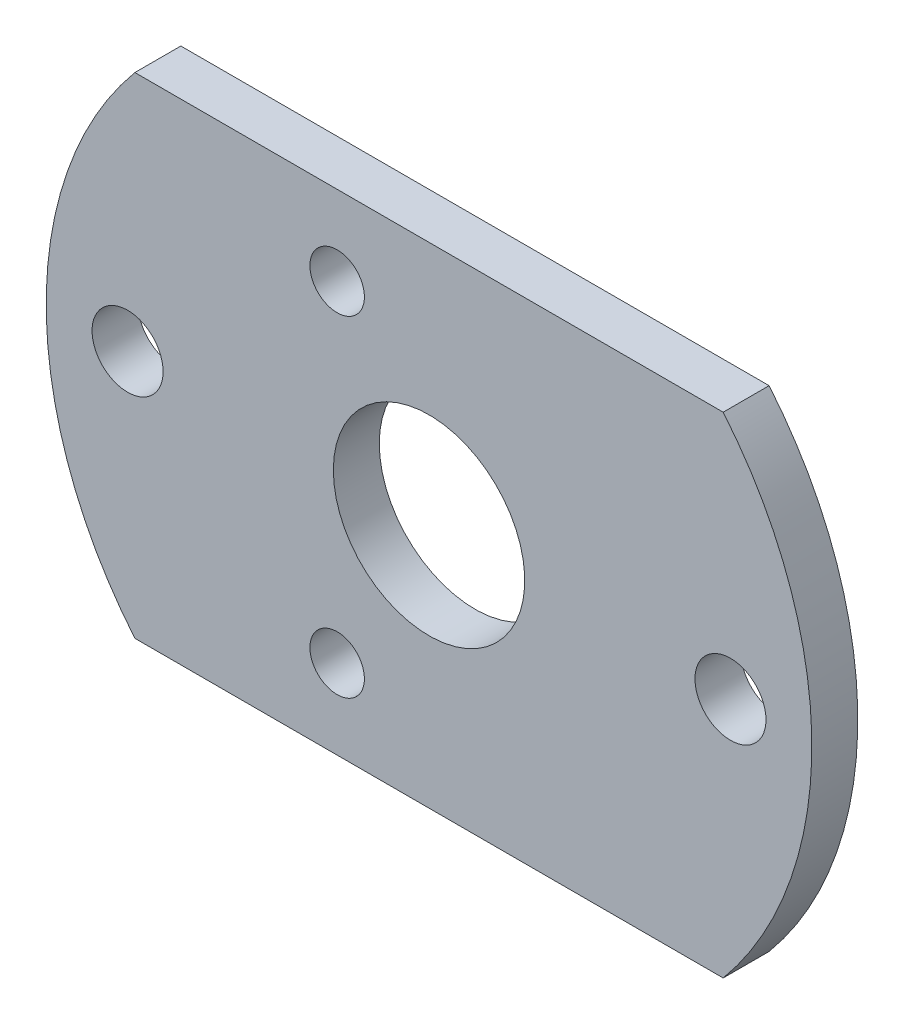
SolidWorks part; units mm, degrees
material "Cast Alloy Steel"
ref_plane "Front Plane" through (0, 0, 0) normal (0, 0, 1) x (1, 0, 0)
ref_plane "Top Plane" through (0, 0, 0) normal (0, 1, 0) x (1, 0, 0)
ref_plane "Right Plane" through (0, 0, 0) normal (1, 0, 0) x (0, 0, -1)
sketch "Sketch1" plane through (0, 0, 0) normal (0, 0, 1) x (1, 0, 0)
  circle A0 centre (0, 0) radius 15.875
  circle A1 centre (0, 0) radius 3.9688
  dimension "D1" = 7.9375
  dimension "D2" = 31.75
extrude "Boss-Extrude1" add sketch "Sketch1" along normal blind 1.905
hole_wizard "MotorClearanceHoles" positions "Sketch5" profile "Sketch4" hole size "#4" standard "ANSI Inch" end condition through all
sketch "Sketch5" plane through (0, 0, 1.905) normal (0, 0, 1) x (1, 0, 0)
  line L0 (0, 0) -> (0, 12.3097) construction
  point P0 (-12.5, 0)
  point P2 (12.5, 0)
  dimension "D1" = 25
sketch "Sketch4" plane through (-12.5, 0, 1.905) normal (1, 0, 0) x (0, -1, 0)
  line L0 (0, 0) -> (0, 1.905)
  line L1 (0, 1.905) -> (1.4732, 1.905)
  line L2 (1.4732, 1.905) -> (1.4732, 0)
  line L5 (1.4732, 0) -> (0, 0)
  line L11 (0, -6.35) -> (0, 107.95) construction
  dimension "Thru Hole Dia." = 2.9464
  dimension "Thru Hole Depth" = 1.905
hole_wizard "EncoderSetScrews" positions "Sketch7" profile "Sketch6" tap size "#4-40" standard "ANSI Inch" end condition through all
sketch "Sketch7" plane through (0, 0, 1.905) normal (0, 0, 1) x (1, 0, 0)
  line L0 (-21.019, 0) -> (-19.6675, 0) construction
  point P0 (-3.81, 6.858)
  point P2 (-3.81, -6.858)
  dimension "D1" = 13.716
  dimension "D2" = 3.81
sketch "Sketch6" plane through (-3.81, 6.858, 1.905) normal (1, 0, 0) x (0, -1, 0)
  line L0 (0, 0) -> (0, 1.905)
  line L1 (0, 1.905) -> (1.1303, 1.905)
  line L2 (1.1303, 1.905) -> (1.1303, 0)
  line L5 (1.1303, 0) -> (0, 0)
  line L11 (0, -6.35) -> (0, 107.95) construction
  dimension "Thru Tap Drill Dia." = 2.2606
  dimension "Thru Tap Drill Depth" = 1.905
cosmetic thread "Hole Thread1" parameters "D2"=2.8448
cosmetic thread "Hole Thread2" parameters "D2"=2.8448
sketch "Sketch8" plane through (0, 0, 1.905) normal (0, 0, 1) x (1, 0, 0)
  line L0 (-12.198, -10.16) -> (12.198, -10.16)
  line L1 (0, 0) -> (-29.8268, 0) construction
  line L2 (-12.198, 10.16) -> (12.198, 10.16)
  arc A0 (-12.198, 10.16) -> (12.198, 10.16) centre (0, 0) cw
  circle A1 centre (0, 0) radius 15.875
  arc A2 (-12.198, -10.16) -> (12.198, -10.16) centre (0, 0) ccw
  dimension "D2" = 10.16
  dimension "D1" = 0
extrude "LinActCutaway" cut sketch "Sketch8" against normal through all
